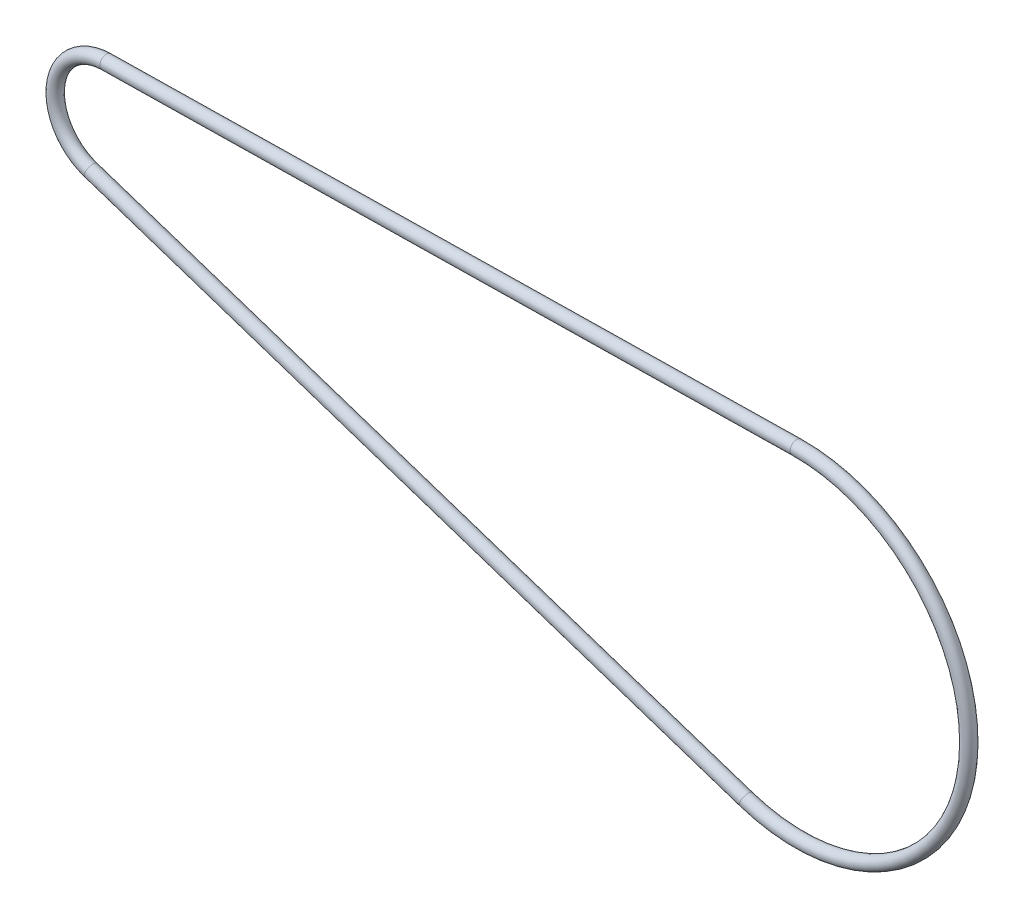
SolidWorks part; units mm, degrees
ref_plane "Alzado" through (0, 0, 0) normal (0, 0, 1) x (1, 0, 0)
ref_plane "Planta" through (0, 0, 0) normal (0, 1, 0) x (1, 0, 0)
ref_plane "Vista lateral" through (0, 0, 0) normal (1, 0, 0) x (0, 0, -1)
ref_plane "Plano_cadena" through (0, 0, 43.5) normal (0, 0, 1) x (1, 0, 0)
sketch "Sk_Cadena" plane through (0, 0, 43.5) normal (0, 0, 1) x (1, 0, 0)
  line L0 (-32.7098, -98.7222) -> (-435.1646, 34.6239)
  line L1 (-425.6276, 96.9957) -> (-1.7147, 103.9859)
  arc A0 (-435.1646, 34.6239) -> (-425.6276, 96.9957) centre (-425.1, 65) cw
  arc A1 (-1.7147, 103.9859) -> (-32.7098, -98.7222) centre (0, 0) cw
sweep "Cadena" add path "Sk_Cadena" circular profile diameter 8 parameters "D3"=8
